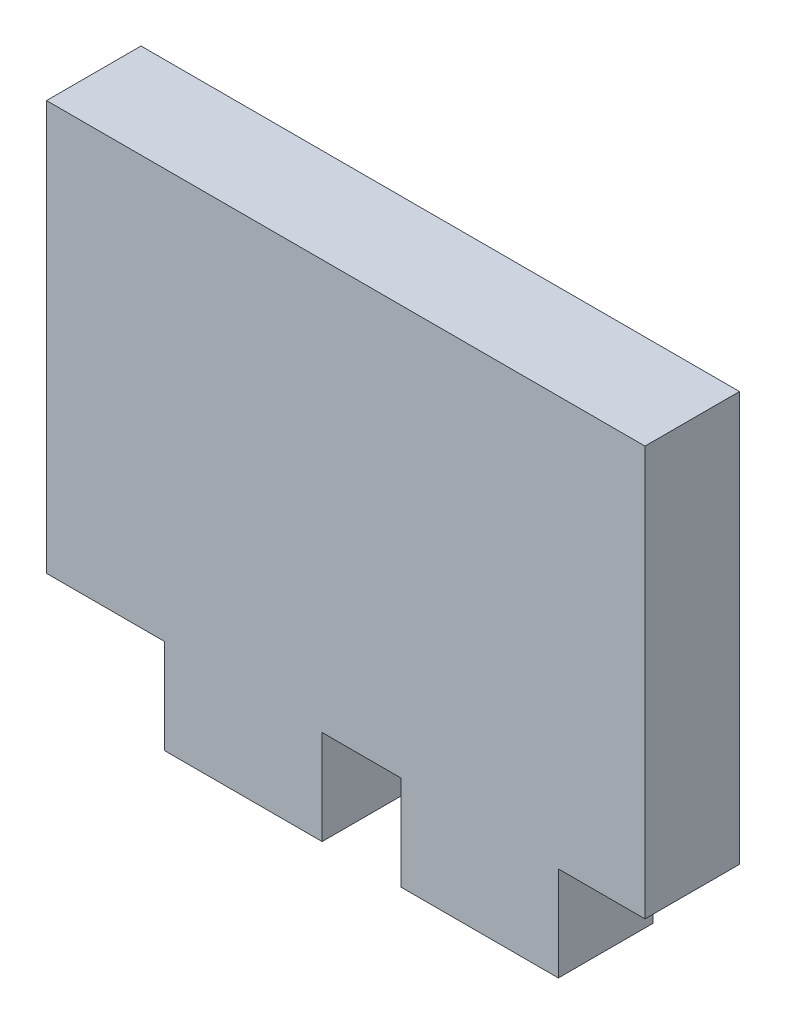
SolidWorks part; units mm, degrees
ref_plane "Front Plane" through (0, 0, 0) normal (0, 0, 1) x (1, 0, 0)
ref_plane "Top Plane" through (0, 0, 0) normal (0, 1, 0) x (1, 0, 0)
ref_plane "Right Plane" through (0, 0, 0) normal (1, 0, 0) x (0, 0, -1)
sketch "Sketch1" plane through (0, 0, 0) normal (0, 0, 1) x (1, 0, 0)
  line L0 (0, 0) -> (10, 0)
  line L1 (10, 0) -> (10, 6)
  line L2 (10, 6) -> (15, 6)
  line L3 (15, 6) -> (15, 0)
  line L4 (15, 0) -> (25, 0)
  line L5 (25, 0) -> (25, 6)
  line L6 (25, 6) -> (30.5, 6)
  line L7 (30.5, 6) -> (30.5, 32)
  line L8 (30.5, 32) -> (-7.5, 32)
  line L9 (-7.5, 32) -> (-7.5, 6)
  line L10 (-7.5, 6) -> (0, 6)
  line L11 (0, 6) -> (0, 0)
  dimension "D1" = 38
  dimension "D2" = 10
  dimension "D3" = 5
  dimension "D4" = 6
  dimension "D5" = 26
  dimension "D6" = 7.5
extrude "Boss-Extrude1" add sketch "Sketch1" along normal blind 6
